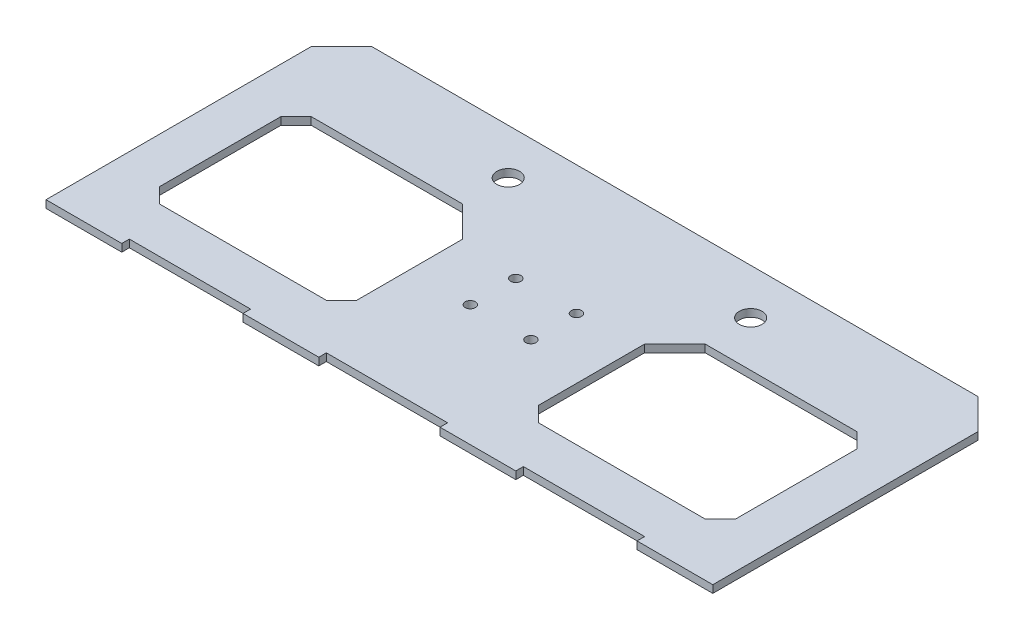
SolidWorks part; units mm, degrees
ref_plane "Plan de face" through (0, 0, 0) normal (0, 0, 1) x (1, 0, 0)
ref_plane "Plan de dessus" through (0, 0, 0) normal (0, 1, 0) x (1, 0, 0)
ref_plane "Plan de droite" through (0, 0, 0) normal (1, 0, 0) x (0, 0, -1)
sketch "Esquisse1" plane through (0, 0, 0) normal (0, 1, 0) x (1, 0, 0)
  line L0 (440, 20) -> (440, 0) construction
  line L1 (0, 0) -> (880, 0) construction
  line L2 (0, 0) -> (0, 250)
  line L3 (240, 250) -> (320, 250)
  line L4 (880, 0) -> (880, 250)
  line L5 (400, 80) -> (480, 80) construction
  line L6 (400, 80) -> (400, 20) construction
  line L7 (400, 20) -> (480, 20) construction
  line L8 (480, 80) -> (480, 20) construction
  line L9 (240, 250) -> (240, 80) construction
  line L10 (240, 80) -> (320, 80) construction
  line L11 (320, 80) -> (320, 250) construction
  line L12 (320, 250) -> (560, 250)
  line L13 (560, 250) -> (560, 80) construction
  line L14 (560, 80) -> (640, 80) construction
  line L15 (640, 80) -> (640, 250) construction
  line L16 (640, 250) -> (880, 250)
  line L17 (240, 250) -> (0, 250)
  line L18 (440, 250) -> (440, 80) construction
  line L19 (320, 80) -> (560, 80) construction
  line L20 (560, 250) -> (640, 250)
  line L21 (280, 250) -> (280, 80) construction
  line L22 (600, 250) -> (600, 80) construction
  line L23 (600, 190) -> (280, 190) construction
  line L24 (0, 0) -> (0, -140)
  line L25 (0, -140) -> (100, -140)
  line L26 (880, -140) -> (880, 0)
  line L27 (260, -140) -> (260, -130)
  line L28 (260, -130) -> (100, -130)
  line L29 (100, -130) -> (100, -140)
  line L30 (440, 80) -> (440, -140) construction
  line L31 (260, -130) -> (360, -130) construction
  line L32 (360, -130) -> (520, -130)
  line L33 (360, -130) -> (360, -140)
  line L34 (780, -130) -> (780, -140)
  line L35 (620, -130) -> (780, -130)
  line L36 (620, -140) -> (620, -130)
  line L37 (520, -130) -> (520, -140)
  line L38 (780, -140) -> (880, -140)
  line L39 (520, -140) -> (620, -140)
  line L40 (260, -140) -> (360, -140)
  circle A0 centre (480, 20) radius 6.75
  circle A1 centre (400, 20) radius 6.75
  circle A2 centre (400, 80) radius 6.75
  circle A3 centre (480, 80) radius 6.75
  circle A4 centre (280, 190) radius 15
  circle A5 centre (600, 190) radius 15
  point P48 (440, -130)
  dimension "D1" = 13.5
  dimension "D2" = 13.5
  dimension "D6" = 13.5
  dimension "D7" = 13.5
  dimension "D14" = 30
  dimension "D15" = 30
  dimension "D3" = 60
  dimension "D4" = 80
  dimension "D5" = 20
  dimension "D8" = 440
  dimension "D9" = 250
  dimension "D10" = 160
  dimension "D11" = 80
  dimension "D12" = 80
  dimension "D13" = 80
  dimension "D16" = 60
  dimension "D17" = 390
  dimension "D18" = 10
  dimension "D19" = 160
  dimension "D20" = 80
  dimension "D21" = 100
extrude "Boss.-Extru.1" add sketch "Esquisse1" along normal blind 10
sketch "Esquisse2" plane through (0, 10, 0) normal (0, 1, 0) x (1, 0, 0)
  line L0 (440, 250) -> (440, -130) construction
  line L1 (800, 130) -> (600, 130)
  line L2 (820, 110) -> (820, -50)
  line L3 (800, -70) -> (580, -70)
  line L4 (560, 90) -> (560, -50)
  line L5 (880, 250) -> (0, 250) construction
  line L6 (360, -130) -> (520, -130) construction
  line L7 (780, -140) -> (880, -140) construction
  line L8 (880, -140) -> (880, 250) construction
  line L9 (600, 130) -> (560, 90)
  line L10 (580, -70) -> (560, -50)
  line L11 (820, -50) -> (800, -70)
  line L12 (800, 130) -> (820, 110)
  line L13 (80, 130) -> (60, 110)
  line L14 (60, -50) -> (80, -70)
  line L15 (300, -70) -> (320, -50)
  line L16 (280, 130) -> (320, 90)
  line L17 (320, 90) -> (320, -50)
  line L18 (80, -70) -> (300, -70)
  line L19 (60, 110) -> (60, -50)
  line L20 (80, 130) -> (280, 130)
  point P0 (820, 130)
  point P1 (560, -70)
  point P2 (820, -70)
  point P3 (560, 130)
  point P30 (320, 130)
  point P31 (60, -70)
  point P32 (320, -70)
  point P33 (60, 130)
  dimension "D1" = 120
  dimension "D2" = 70
  dimension "D3" = 60
  dimension "D4" = 120
extrude "Enlèv. mat.-Extru.1" cut sketch "Esquisse2" against normal blind 10
chamfer "Chanfrein1" distance 40 angle 45 2 edges at (880, 5, -250) (0, 5, -250)
